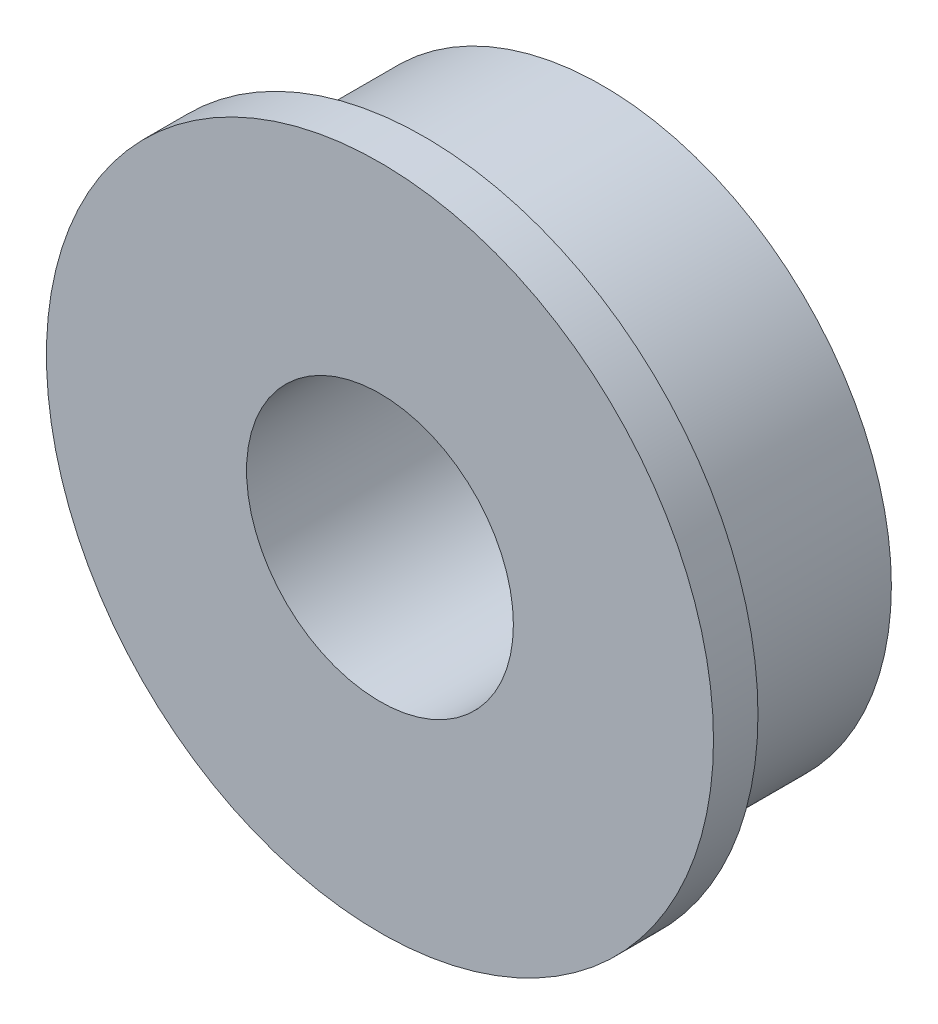
SolidWorks part; units mm, degrees
ref_plane "Front Plane" through (0, 0, 0) normal (0, 0, 1) x (1, 0, 0)
ref_plane "Top Plane" through (0, 0, 0) normal (0, 1, 0) x (1, 0, 0)
ref_plane "Right Plane" through (0, 0, 0) normal (1, 0, 0) x (0, 0, -1)
sketch "Sketch1" plane through (0, 0, 0) normal (1, 0, 0) x (0, 0, -1)
  line L0 (0, 0) -> (9.1457, 0) construction
  line L1 (0, 3) -> (0, 7.5)
  line L2 (0, 7.5) -> (1, 7.5)
  line L3 (1, 7.5) -> (1, 6.5)
  line L4 (1, 6.5) -> (5, 6.5)
  line L5 (5, 6.5) -> (5, 3)
  line L6 (5, 3) -> (0, 3)
  dimension "D1" = 3
  dimension "D2" = 6.5
  dimension "D3" = 7.5
  dimension "D4" = 5
  dimension "D5" = 1
revolve "686ZZ" add sketch "Sketch1" angle 360 about L0
